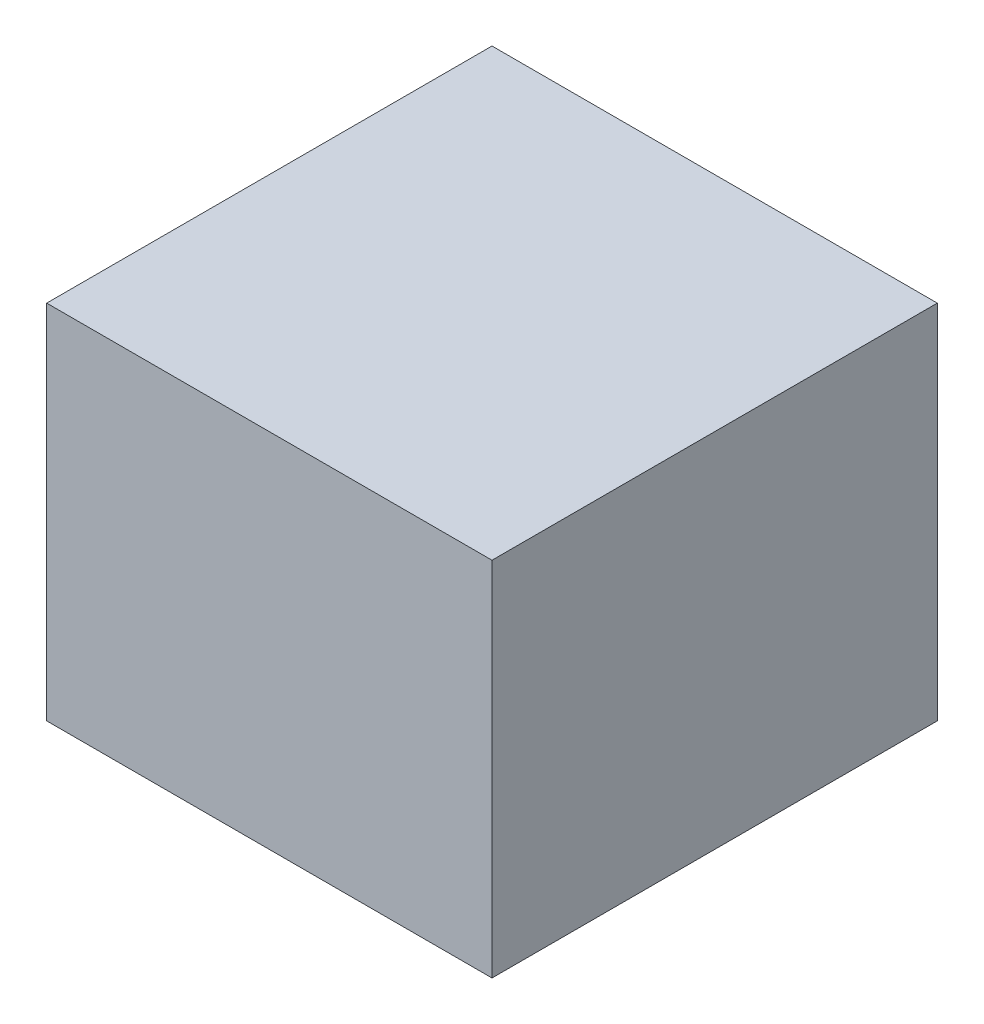
SolidWorks part; units mm, degrees
ref_plane "Płaszczyzna przednia" through (0, 0, 0) normal (0, 0, 1) x (1, 0, 0)
ref_plane "Płaszczyzna górna" through (0, 0, 0) normal (0, 1, 0) x (1, 0, 0)
ref_plane "Płaszczyzna prawa" through (0, 0, 0) normal (1, 0, 0) x (0, 0, -1)
sketch "Szkic1" plane through (0, 0, 0) normal (0, 1, 0) x (1, 0, 0)
  line L1 (-4, -4) -> (4, -4)
  line L2 (-4, -4) -> (-4, 4)
  line L3 (-4, 4) -> (4, 4)
  line L4 (4, -4) -> (4, 4)
  line L5 (-4, -4) -> (4, 4) construction
  line L6 (-4, 4) -> (4, -4) construction
  point P0 (0, 0)
  dimension "D1" = 8
extrude "Dodanie-wyciągnięcie1" add sketch "Szkic1" along normal blind 6.5
